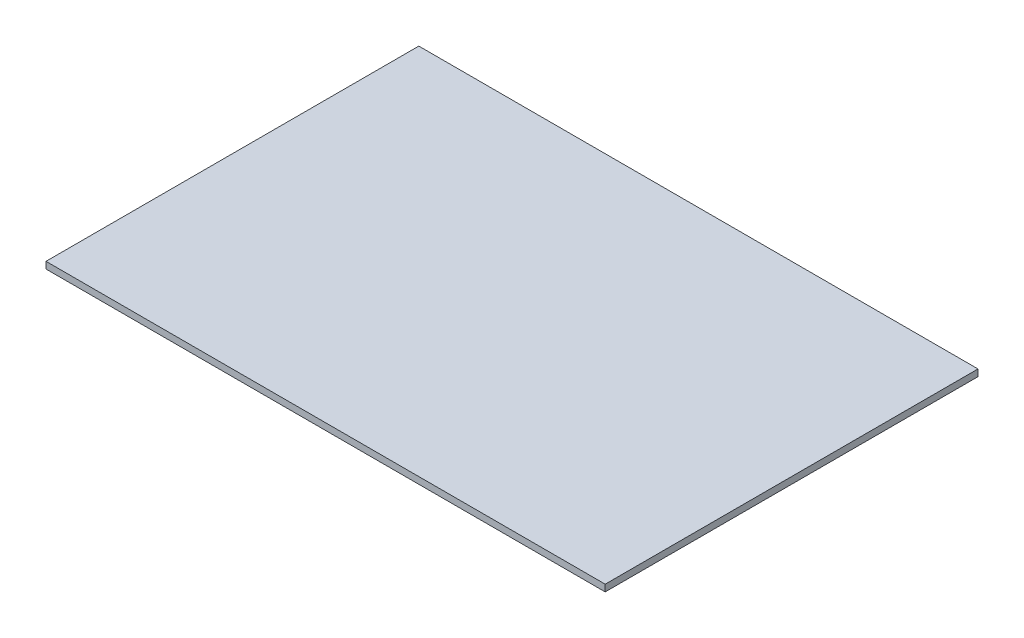
SolidWorks part; units mm, degrees
ref_plane "Front Plane" through (0, 0, 0) normal (0, 0, 1) x (1, 0, 0)
ref_plane "Top Plane" through (0, 0, 0) normal (0, 1, 0) x (1, 0, 0)
ref_plane "Right Plane" through (0, 0, 0) normal (1, 0, 0) x (0, 0, -1)
sketch "Esquisse1" plane through (0, 0, 0) normal (0, 1, 0) x (1, 0, 0)
  line L1 (-750, 500) -> (750, 500)
  line L2 (-750, 500) -> (-750, -500)
  line L3 (-750, -500) -> (750, -500)
  line L4 (750, 500) -> (750, -500)
  line L5 (-750, 500) -> (750, -500) construction
  line L6 (-750, -500) -> (750, 500) construction
  point P0 (0, 0)
extrude "Boss.-Extru.1" add sketch "Esquisse1" along normal blind 18
